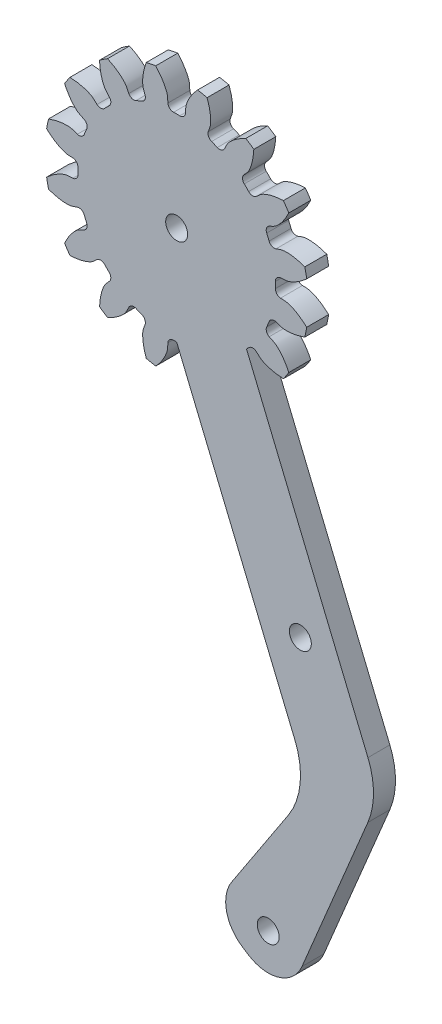
SolidWorks part; units mm, degrees
ref_plane "Front" through (0, 0, 0) normal (0, 0, 1) x (1, 0, 0)
ref_plane "Top" through (0, 0, 0) normal (0, 1, 0) x (1, 0, 0)
ref_plane "Right" through (0, 0, 0) normal (1, 0, 0) x (0, 0, -1)
ref_axis "Axis1" through (0, 0, -80.9) along (0, 0, 1)
sketch "草图1" plane through (0, 0, 0) normal (0, 0, 1) x (1, 0, 0)
  circle A0 centre (0, 0) radius 18
extrude "LaShenA" add sketch "草图1" along normal blind 30
sketch "SketchA" plane through (0, 0, 30) normal (0, 0, 1) x (1, 0, 0)
  line L0 (0, 0) -> (0, 18) construction
  arc A0 (0.4232, 13.4934) -> (-0.4232, 13.4934) centre (0, 0) ccw
  arc A1 (3.858, 18.7275) -> (-3.858, 18.7275) centre (0, 0) ccw
  arc A2 (-0.4232, 13.4934) -> (-1.2044, 14.1898) centre (-0.447, 14.253) cw
  arc A3 (1.2044, 14.1898) -> (0.4232, 13.4934) centre (0.447, 14.253) cw
  circle A4 centre (0, 0) radius 15.0351 construction
  circle A5 centre (0, 0) radius 18 construction
  circle A6 centre (0, 0) radius 13.5 construction
  circle A7 centre (0, 0) radius 16 construction
  spline S0 degree 3 poles (1.2044, 14.1898) (1.2266, 14.4552) (1.2138, 14.7739) (1.2737, 15.1106) (1.2991, 15.2114) (1.3214, 15.2911) (1.3499, 15.3823) (1.3851, 15.4846) (1.4278, 15.5978) (1.4786, 15.7214) (1.5382, 15.8552) (1.6071, 15.9987) (1.686, 16.1514) (1.7754, 16.3129) (1.876, 16.4827) (1.9884, 16.6603) (2.1129, 16.8451) (2.2502, 17.0365) (2.4007, 17.234) (2.5649, 17.4369) (2.7432, 17.6446) (2.9361, 17.8564) (3.1439, 18.0718) (3.4474, 18.3685) (3.6895, 18.585) (3.858, 18.7275) knots 0.122308 0.122308 0.122308 0.122308 0.250611 0.276296 0.287604 0.300968 0.316388 0.333864 0.353395 0.374983 0.398627 0.424327 0.452082 0.481894 0.513762 0.547685 0.583665 0.6217 0.661792 0.703939 0.748143 0.794402 0.842718 0.893089 1 1 1 1
  spline S1 degree 3 poles (-1.2044, 14.1898) (-1.2266, 14.4552) (-1.2138, 14.7739) (-1.2737, 15.1106) (-1.2991, 15.2114) (-1.3214, 15.2911) (-1.3499, 15.3823) (-1.3851, 15.4846) (-1.4278, 15.5978) (-1.4786, 15.7214) (-1.5382, 15.8552) (-1.6071, 15.9987) (-1.686, 16.1514) (-1.7754, 16.3129) (-1.876, 16.4827) (-1.9884, 16.6603) (-2.1129, 16.8451) (-2.2502, 17.0365) (-2.4007, 17.234) (-2.5649, 17.4369) (-2.7432, 17.6446) (-2.9361, 17.8564) (-3.1439, 18.0718) (-3.4474, 18.3685) (-3.6895, 18.585) (-3.858, 18.7275) knots 0.122308 0.122308 0.122308 0.122308 0.250611 0.276296 0.287604 0.300968 0.316388 0.333864 0.353395 0.374983 0.398627 0.424327 0.452082 0.481894 0.513762 0.547685 0.583665 0.6217 0.661792 0.703939 0.748143 0.794402 0.842718 0.893089 1 1 1 1
  dimension "D1" = 0.76
  dimension "Db" = 30.0702
  dimension "Da" = 36
  dimension "Df" = 27
  dimension "Dn" = 32
extrude "Cut-ExtrudeA" cut sketch "SketchA" against normal blind 30
pattern_circular "www.KYTool.cn" count 16 over 360 about axis through (0, 0, -80.9) along (0, 0, 1) of "Cut-ExtrudeA"
sketch "草图3" plane through (0, 0, 0) normal (0, 1, 0) x (1, 0, 0)
  line L0 (17.7715, -30) -> (17.7715, 0) construction
  line L1 (-17.7715, 0) -> (17.7715, 0)
  line L2 (-17.7715, 0) -> (-17.7715, -27)
  line L3 (-17.7715, -27) -> (17.7715, -27)
  line L4 (17.7715, 0) -> (17.7715, -27)
extrude "切除-拉伸2" cut sketch "草图3" against normal mid plane 60
sketch "草图4" plane through (0, 0, 30) normal (0, 0, 1) x (1, 0, 0)
  circle A0 centre (0, 0) radius 1.5
extrude "切除-拉伸3" cut sketch "草图4" against normal blind 60
sketch "草图5" plane through (0, 0, 30) normal (0, 0, 1) x (1, 0, 0)
  line L2 (0, -13.5) -> (9.5459, -9.5459)
  line L4 (15.2802, -61.8354) -> (7.5186, -73.6486)
  line L10 (0, -13.5) -> (9.5459, -9.5459)
  line L11 (0, -13.5) -> (16.1616, -52.5174)
  line L12 (9.5459, -9.5459) -> (26.1422, -49.6129)
  line L15 (8.9517, -80.5729) -> (9.7653, -81.1075)
  line L16 (26.1308, -57.2939) -> (17.1246, -78.8558)
  arc A2 (-0.4232, -13.4934) -> (0.4232, -13.4934) centre (0, 0) ccw construction
  arc A3 (9.242, -9.8405) -> (9.8405, -9.242) centre (0, 0) ccw construction
  arc A4 (16.1616, -52.5174) -> (15.2802, -61.8354) centre (6.9228, -56.3443) cw
  arc A5 (26.1308, -57.2939) -> (26.1422, -49.6129) centre (16.9034, -53.4397) ccw
  arc A6 (9.7653, -81.1075) -> (17.1246, -78.8558) centre (12.5109, -76.9288) ccw
  arc A7 (7.5186, -73.6486) -> (8.9517, -80.5729) centre (11.6973, -76.3942) ccw
  circle A8 centre (12.5109, -76.9288) radius 1.5
  circle A9 centre (16.9034, -40.0175) radius 1.5
extrude "凸台-拉伸3" add sketch "草图5" against normal blind 3 contours L4 A7 L15 A6 L16 A5 L12 L2 L11 A4 A9 A8
